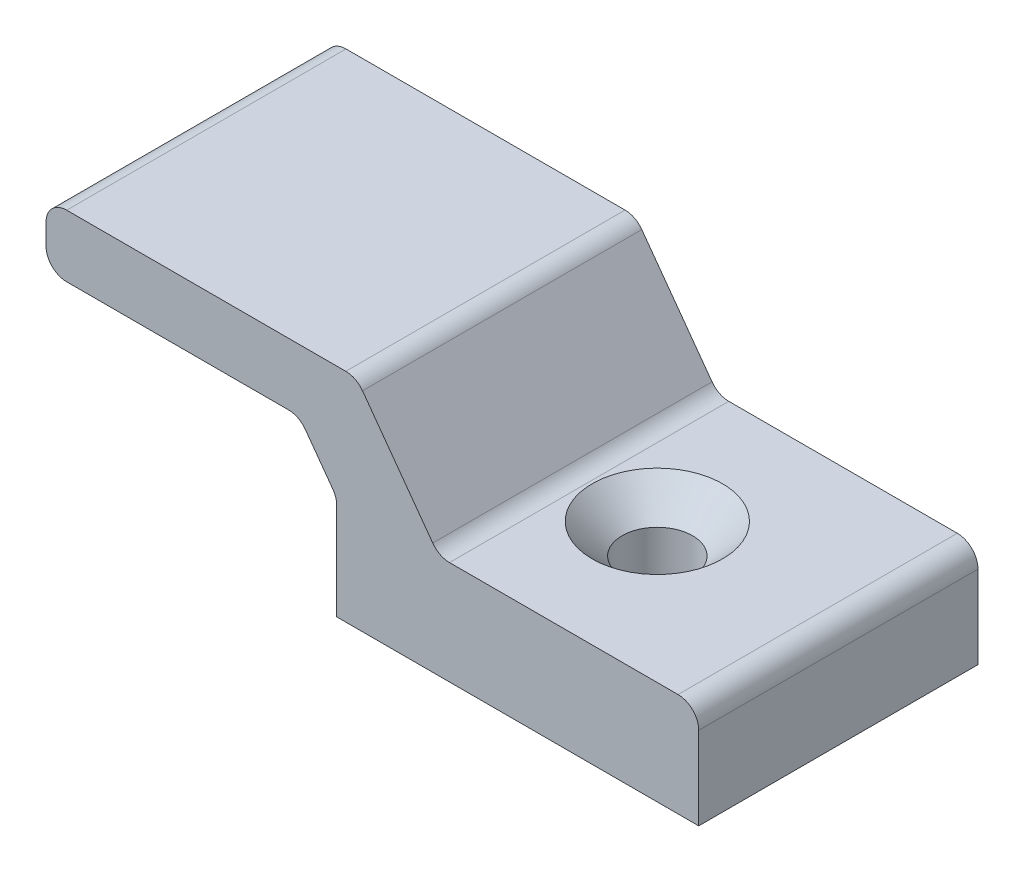
SolidWorks part; units mm, degrees
material "3.1355 (EN-AW 2024)"
ref_plane "Спереди" through (0, 0, 0) normal (0, 0, 1) x (1, 0, 0)
ref_plane "Сверху" through (0, 0, 0) normal (0, 1, 0) x (1, 0, 0)
ref_plane "Справа" through (0, 0, 0) normal (1, 0, 0) x (0, 0, -1)
sketch "Эскиз1" plane through (0, 0, 0) normal (0, 0, 1) x (1, 0, 0)
  line L0 (8.75, 0) -> (-8.75, 0)
  line L1 (-8.75, 0) -> (-8.75, 5)
  line L2 (-8.75, 5) -> (-10.565, 7.5)
  line L3 (-10.565, 7.5) -> (-22.8, 7.5)
  line L4 (-22.8, 7.5) -> (-22.8, 10.5)
  line L5 (-22.8, 10.5) -> (-7.8, 10.5)
  line L6 (-7.8, 10.5) -> (-3.807, 5)
  line L8 (-3.807, 5) -> (8.75, 5)
  line L9 (8.75, 5) -> (8.75, 0)
  point P8 (0, 0)
  point P9 (-3.3998, 5)
  point P16 (-15.3, 10.5)
  dimension "D1" = 17.5
  dimension "D2" = 5
  dimension "D3" = 4
  dimension "D4" = 3
  dimension "D7" = 10.5
  dimension "D8" = 15
  dimension "D9" = 15.3
extrude "База" add sketch "Эскиз1" along normal blind 13.5
fillet "Скругление1" radius 1 7 edges at (8.75, 5, 6.75) (-8.75, 5, 6.75) (-10.565, 7.5, 6.75) (-3.807, 5, 6.75) (-22.8, 7.5, 6.75) (-22.8, 10.5, 6.75) (-7.8, 10.5, 6.75)
hole_wizard "Крепление-M3" positions "Эскиз2" profile "Эскиз3" countersink size "M3" standard "DIN" end condition through all
sketch "Эскиз2" plane through (0, 5, 0) normal (0, 1, 0) x (1, 0, 0)
  line L0 (8.75, -13.5) -> (8.75, 0) construction
  point P0 (0, -6.75)
  point P5 (8.75, -6.75)
sketch "Эскиз3" plane through (0, 5, 6.75) normal (1, 0, 0) x (0, 0, 1)
  line L0 (0, 0) -> (0, 5)
  line L1 (0, 5) -> (1.7, 5)
  line L2 (1.7, 5) -> (1.7, 1.45)
  line L3 (1.7, 1.45) -> (3.15, 0)
  line L5 (3.15, 0) -> (0, 0)
  line L6 (-1.7, 1.45) -> (-3.15, 0) construction
  line L11 (0, -6.35) -> (0, 107.95) construction
  dimension "Диаметр сквозного отверстия" = 3.4
  dimension "Глубина сквозного отверстия" = 5
  dimension "Диаметр передней зенковки" = 6.3
  dimension "Угол передней зенковки" = 90
